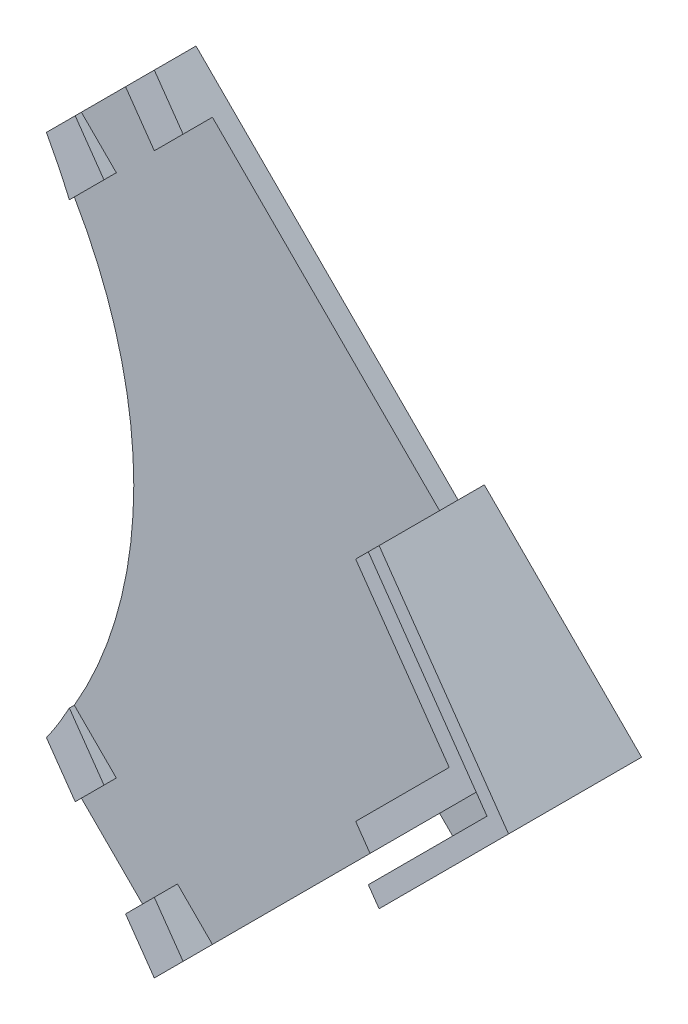
SolidWorks part; units mm, degrees
ref_plane "前视基准面" through (0, 0, 0) normal (0, 0, 1) x (1, 0, 0)
ref_plane "上视基准面" through (0, 0, 0) normal (0, 1, 0) x (1, 0, 0)
ref_plane "右视基准面" through (0, 0, 0) normal (1, 0, 0) x (0, 0, -1)
sketch "Closed_bottom_plate_3mm_sketch" plane through (0, 0, 0) normal (0, 0, 1) x (1, 0, 0)
  line L0 (77.7817, -63.6396) -> (141.4214, 0)
  line L1 (141.4214, 0) -> (77.7817, 63.6396)
  line L2 (77.7817, 63.6396) -> (56.5685, 42.4264)
  line L3 (56.5685, -42.4264) -> (77.7817, -63.6396)
  arc A0 (56.5685, 42.4264) -> (56.5685, -42.4264) centre (0, 0) cw
extrude "Closed_bottom_plate_3mm" add sketch "Closed_bottom_plate_3mm_sketch" along normal blind 3
sketch "Foot1_curved_R70p71_sketch" plane through (0, 0, 0) normal (0, 0, 1) x (1, 0, 0)
  line L0 (62.2254, 48.0833) -> (67.8823, 42.4264)
  line L1 (67.8823, 42.4264) -> (61.0808, 35.6249)
  line L2 (56.5685, 42.4264) -> (62.2254, 48.0833)
  arc A0 (61.0808, 35.6249) -> (56.5685, 42.4264) centre (0, 0) ccw
extrude "Foot1_curved_R70p71" add sketch "Foot1_curved_R70p71_sketch" along normal blind 20
sketch "Foot2_curved_R70p71_sketch" plane through (0, 0, 0) normal (0, 0, 1) x (1, 0, 0)
  line L0 (62.2254, -48.0833) -> (67.8823, -42.4264)
  line L1 (67.8823, -42.4264) -> (61.0808, -35.6249)
  line L2 (56.5685, -42.4264) -> (62.2254, -48.0833)
  arc A0 (61.0808, -35.6249) -> (56.5685, -42.4264) centre (0, 0) cw
extrude "Foot2_curved_R70p71" add sketch "Foot2_curved_R70p71_sketch" along normal blind 20
sketch "Pad4_C_blank_sketch" plane through (0, 0, 0) normal (0, 0, 1) x (1, 0, 0)
  line L0 (72.1249, 57.9828) -> (77.7817, 52.3259)
  line L1 (77.7817, 52.3259) -> (83.4386, 57.9828)
  line L2 (83.4386, 57.9828) -> (77.7817, 63.6396)
  line L3 (77.7817, 63.6396) -> (72.1249, 57.9828)
extrude "Pad4_C_blank" add sketch "Pad4_C_blank_sketch" along normal blind 20
sketch "Pad5_A_blank_sketch" plane through (0, 0, 0) normal (0, 0, 1) x (1, 0, 0)
  line L0 (72.1249, -57.9828) -> (77.7817, -63.6396)
  line L1 (77.7817, -63.6396) -> (83.4386, -57.9828)
  line L2 (83.4386, -57.9828) -> (77.7817, -52.3259)
  line L3 (77.7817, -52.3259) -> (72.1249, -57.9828)
extrude "Pad5_A_blank" add sketch "Pad5_A_blank_sketch" along normal blind 20
sketch "Slot_backing_inside_north_sketch" plane through (0, 0, 0) normal (0, 0, 1) x (1, 0, 0)
  line L0 (117.3797, 18.3848) -> (138.5929, -2.8284)
  line L1 (138.5929, -2.8284) -> (141.4214, 0)
  line L2 (141.4214, 0) -> (120.2082, 21.2132)
  line L3 (120.2082, 21.2132) -> (117.3797, 18.3848)
extrude "Slot_backing_inside_north" add sketch "Slot_backing_inside_north_sketch" along normal blind 22
sketch "Slot_backing_inside_east_sketch" plane through (0, 0, 0) normal (0, 0, 1) x (1, 0, 0)
  line L0 (117.3797, -18.3848) -> (120.2082, -21.2132)
  line L1 (120.2082, -21.2132) -> (141.4214, 0)
  line L2 (141.4214, 0) -> (138.5929, 2.8284)
  line L3 (138.5929, 2.8284) -> (117.3797, -18.3848)
extrude "Slot_backing_inside_east" add sketch "Slot_backing_inside_east_sketch" along normal blind 22
sketch "Top_outer_plane_sketch" plane through (0, 0, 0) normal (0, 1, 0) x (1, 0, 0)
  line L0 (-100, 24.6777) -> (250, -37.1942)
  line L1 (250, -37.1942) -> (250, -100)
  line L2 (250, -100) -> (-100, -100)
  line L3 (-100, -100) -> (-100, 24.6777)
extrude "Top_outer_plane" cut sketch "Top_outer_plane_sketch" against normal through all and the other way through all
sketch "Slot_base_north_sketch" plane through (0, 0, 0) normal (0, 0, 1) x (1, 0, 0)
  line L0 (117.3797, 18.3848) -> (142.8356, -7.0711)
  line L1 (142.8356, -7.0711) -> (149.9066, 0)
  line L2 (149.9066, 0) -> (124.4508, 25.4558)
  line L3 (124.4508, 25.4558) -> (117.3797, 18.3848)
extrude "Slot_base_north" add sketch "Slot_base_north_sketch" along normal blind 3
sketch "Slot_base_east_sketch" plane through (0, 0, 0) normal (0, 0, 1) x (1, 0, 0)
  line L0 (117.3797, -18.3848) -> (124.4508, -25.4558)
  line L1 (124.4508, -25.4558) -> (149.9066, 0)
  line L2 (149.9066, 0) -> (142.8356, 7.0711)
  line L3 (142.8356, 7.0711) -> (117.3797, -18.3848)
extrude "Slot_base_east" add sketch "Slot_base_east_sketch" along normal blind 3
sketch "Slot_outer_north_sketch" plane through (0, 0, 0) normal (0, 0, 1) x (1, 0, 0)
  line L0 (122.3295, 23.3345) -> (147.7853, -2.1213)
  line L1 (147.7853, -2.1213) -> (149.9066, 0)
  line L2 (149.9066, 0) -> (124.4508, 25.4558)
  line L3 (124.4508, 25.4558) -> (122.3295, 23.3345)
extrude "Slot_outer_north" add sketch "Slot_outer_north_sketch" along normal blind 22
sketch "Slot_outer_east_sketch" plane through (0, 0, 0) normal (0, 0, 1) x (1, 0, 0)
  line L0 (122.3295, -23.3345) -> (124.4508, -25.4558)
  line L1 (124.4508, -25.4558) -> (149.9066, 0)
  line L2 (149.9066, 0) -> (147.7853, 2.1213)
  line L3 (147.7853, 2.1213) -> (122.3295, -23.3345)
extrude "Slot_outer_east" add sketch "Slot_outer_east_sketch" along normal blind 22
sketch "草图13" plane through (0, 0, 0) normal (0, 1, 0) x (1, 0, 0)
  line L0 (-100, 22.6467) -> (250, -39.2252)
  line L1 (250, -39.2252) -> (250, -100)
  line L2 (250, -100) -> (-100, -100)
  line L3 (-100, -100) -> (-100, 22.6467)
extrude "切除-拉伸2" cut sketch "草图13" against normal through all and the other way through all
